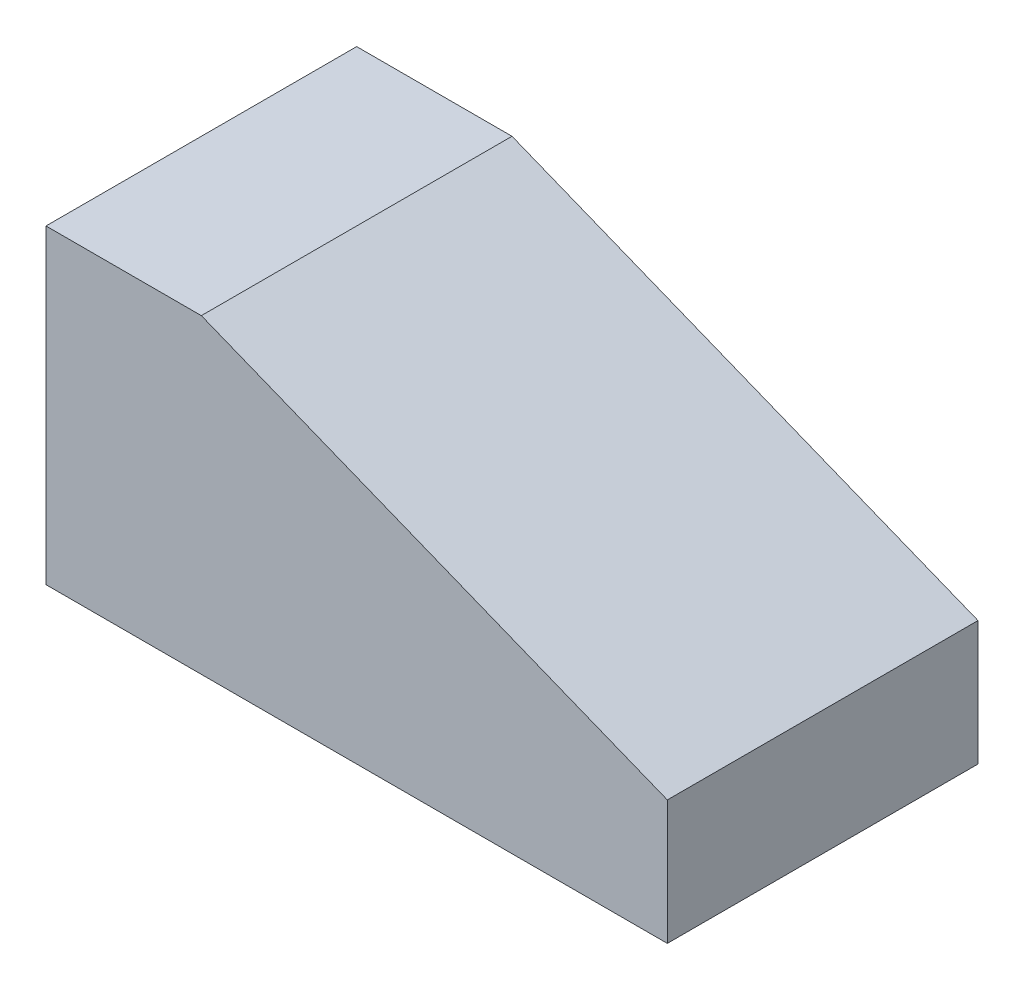
SolidWorks part; units mm, degrees
ref_plane "정면" through (0, 0, 0) normal (0, 0, 1) x (1, 0, 0)
ref_plane "윗면" through (0, 0, 0) normal (0, 1, 0) x (1, 0, 0)
ref_plane "우측면" through (0, 0, 0) normal (1, 0, 0) x (0, 0, -1)
sketch "스케치1" plane through (0, 0, 0) normal (0, 0, 1) x (1, 0, 0)
  line L0 (0, 0) -> (100, 0)
  line L1 (100, 0) -> (100, 20)
  line L2 (100, 20) -> (25, 50)
  line L3 (25, 50) -> (0, 50)
  line L4 (0, 50) -> (0, 0)
  dimension "D1" = 100
  dimension "D2" = 20
  dimension "D3" = 25
  dimension "D4" = 50
extrude "보스-돌출1" add sketch "스케치1" along normal blind 50
